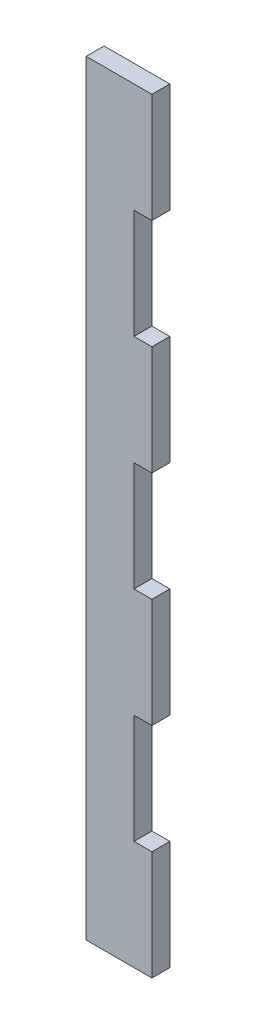
SolidWorks part; units mm, degrees
ref_plane "Front Plane" through (0, 0, 0) normal (0, 0, 1) x (1, 0, 0)
ref_plane "Top Plane" through (0, 0, 0) normal (0, 1, 0) x (1, 0, 0)
ref_plane "Right Plane" through (0, 0, 0) normal (1, 0, 0) x (0, 0, -1)
sketch "Sketch1" plane through (0, 0, 0) normal (0, 0, 1) x (1, 0, 0)
  line L0 (0, 101.6) -> (0, -101.6) construction
  line L1 (-6.35, 101.6) -> (6.35, 101.6)
  line L2 (-6.35, 101.6) -> (-6.35, -101.6)
  line L3 (-6.35, -101.6) -> (6.35, -101.6)
  line L4 (6.35, 101.6) -> (6.35, -101.6)
  line L5 (6.35, 72.5714) -> (6.35, 43.5429)
  line L6 (6.35, 101.6) -> (11.1125, 101.6)
  line L7 (6.35, 101.6) -> (6.35, 72.5714)
  line L8 (6.35, 72.5714) -> (11.1125, 72.5714)
  line L9 (11.1125, 101.6) -> (11.1125, 72.5714)
  line L10 (6.35, 72.5714) -> (11.1125, 72.5714)
  line L11 (11.1125, 72.5714) -> (11.1125, 43.5429)
  line L12 (6.35, 43.5429) -> (11.1125, 43.5429)
  line L13 (6.35, 43.5429) -> (6.35, 14.5143)
  line L14 (6.35, 43.5429) -> (11.1125, 43.5429)
  line L15 (11.1125, 43.5429) -> (11.1125, 14.5143)
  line L16 (6.35, 14.5143) -> (11.1125, 14.5143)
  line L17 (6.35, 14.5143) -> (6.35, -14.5143)
  line L18 (6.35, 14.5143) -> (11.1125, 14.5143)
  line L19 (11.1125, 14.5143) -> (11.1125, -14.5143)
  line L20 (6.35, -14.5143) -> (11.1125, -14.5143)
  line L21 (6.35, -14.5143) -> (6.35, -43.5429)
  line L22 (6.35, -14.5143) -> (11.1125, -14.5143)
  line L23 (11.1125, -14.5143) -> (11.1125, -43.5429)
  line L24 (6.35, -43.5429) -> (11.1125, -43.5429)
  line L25 (6.35, -43.5429) -> (6.35, -72.5714)
  line L26 (6.35, -43.5429) -> (11.1125, -43.5429)
  line L27 (11.1125, -43.5429) -> (11.1125, -72.5714)
  line L28 (6.35, -72.5714) -> (11.1125, -72.5714)
  line L29 (6.35, -72.5714) -> (6.35, -101.6)
  line L30 (6.35, -72.5714) -> (11.1125, -72.5714)
  line L31 (11.1125, -72.5714) -> (11.1125, -101.6)
  line L32 (6.35, -101.6) -> (11.1125, -101.6)
  point P6 (0, 0)
  dimension "D2" = 12.7
  dimension "D1" = 203.2
  dimension "D3" = 29.0286
  dimension "D4" = 4.7625
  dimension "D5" = 7
extrude "Boss-Extrude1" add sketch "Sketch1" along normal blind 4.7625 contours L0 L1 L2 L3 | L1 L0 L3 L4 | L9 L6 L4 L8 | L4 L16 L15 L12 | L4 L24 L23 L20 | L4 L32 L31 L28
equation "\"Height\"= 12in"
equation "\"Depth\"= 7in"
equation "\"WallThickness\"= 0.1875in"
equation "\"FloorThickness\"= 0.1875in"
equation "\"Width\" = 30in"
equation "\"D1@Boss-Extrude1\"=\"WallThickness\""
equation "\"D3@Sketch1\"=\"D1@Sketch1\"/\"D5@Sketch1\""
equation "\"D4@Sketch1\"=\"WallThickness\""
